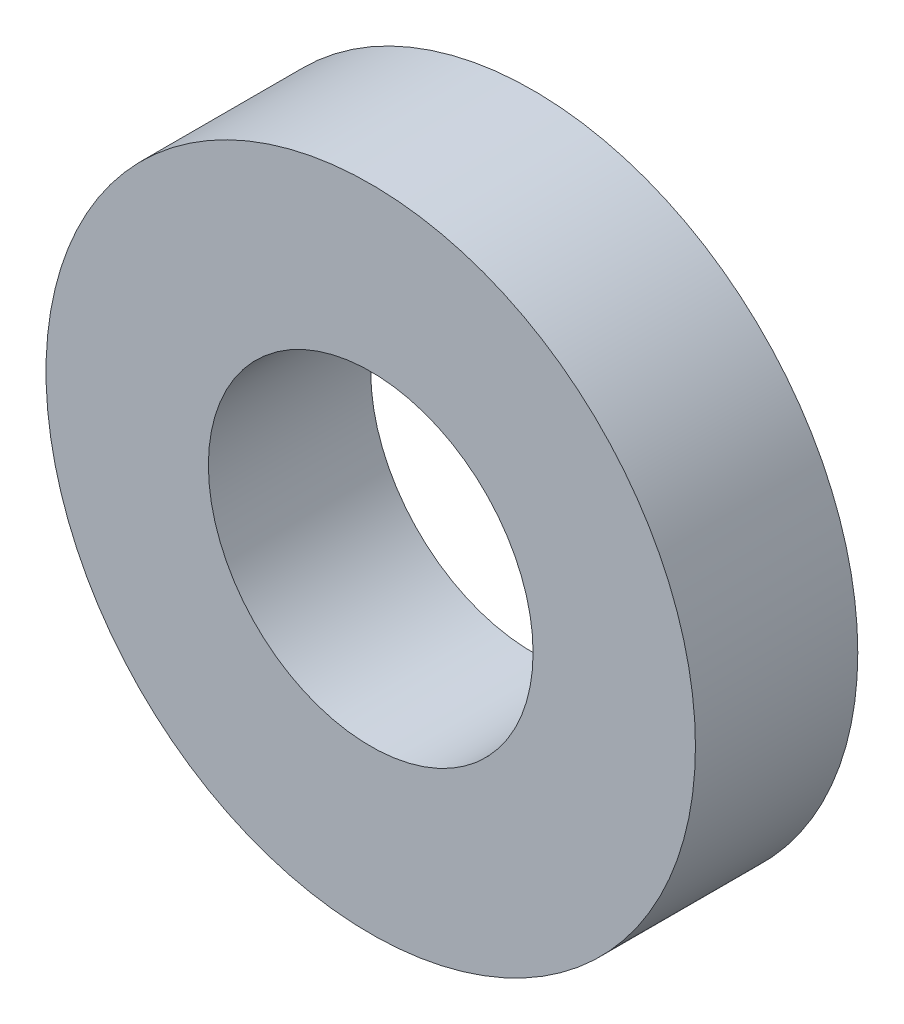
SolidWorks part; units mm, degrees
ref_plane "Front Plane" through (0, 0, 0) normal (0, 0, 1) x (1, 0, 0)
ref_plane "Top Plane" through (0, 0, 0) normal (0, 1, 0) x (1, 0, 0)
ref_plane "Right Plane" through (0, 0, 0) normal (1, 0, 0) x (0, 0, -1)
sketch "Sketch2" plane through (0, 0, 0) normal (0, 0, 1) x (1, 0, 0)
  circle A0 centre (0, 0) radius 2
  circle A1 centre (0, 0) radius 1
  dimension "D1" = 2
  dimension "D2" = 4
extrude "Boss-Extrude1" add sketch "Sketch2" along normal blind 1
